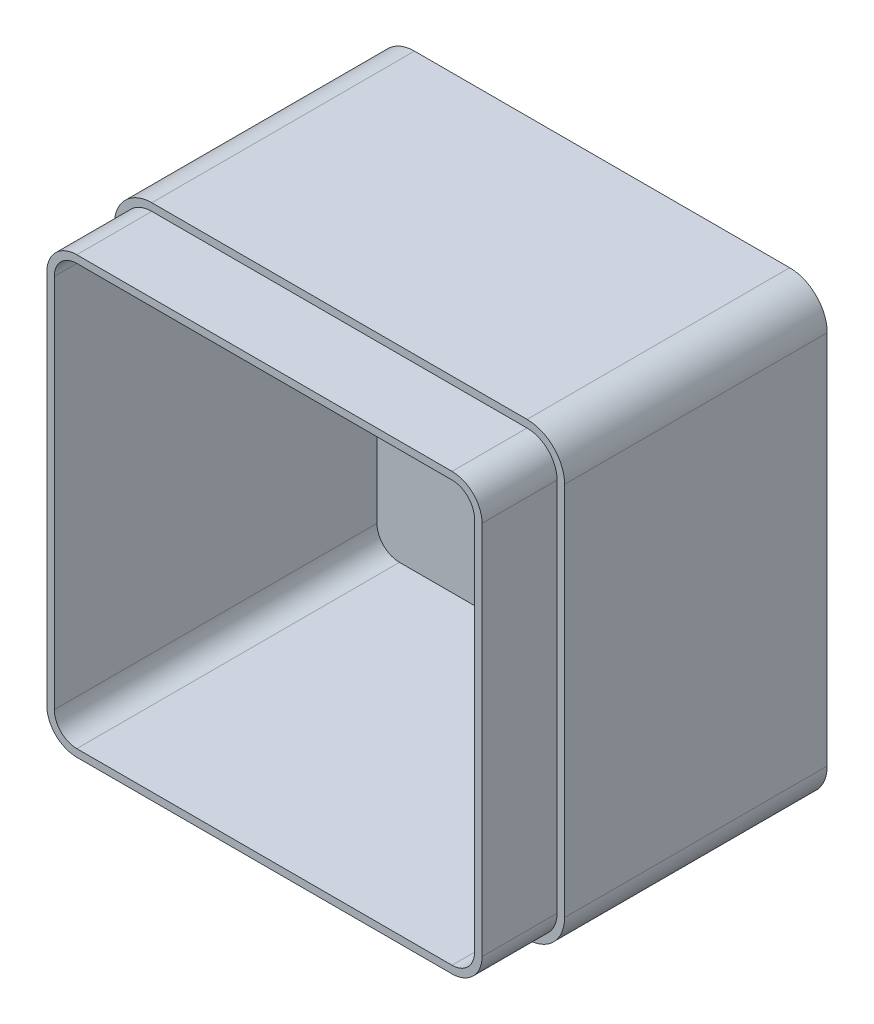
SolidWorks part; units mm, degrees
ref_plane "Спереди" through (0, 0, 0) normal (0, 0, 1) x (1, 0, 0)
ref_plane "Сверху" through (0, 0, 0) normal (0, 1, 0) x (1, 0, 0)
ref_plane "Справа" through (0, 0, 0) normal (1, 0, 0) x (0, 0, -1)
sketch "Эскиз1" plane through (0, 0, 0) normal (0, 0, 1) x (1, 0, 0)
  line L1 (0, 0) -> (120, 0)
  line L2 (0, 0) -> (0, 120)
  line L3 (0, 120) -> (120, 120)
  line L4 (120, 0) -> (120, 120)
  dimension "D1" = 120
  dimension "D2" = 120
extrude "Бобышка-Вытянуть1" add sketch "Эскиз1" along normal blind 90
fillet "Скругление1" radius 10 4 edges at (120, 120, 45) (0, 120, 45) (0, 0, 45) (120, 0, 45)
shell "Оболочка1" thickness 4
sketch "Эскиз2" plane through (0, 0, 90) normal (0, 0, 1) x (1, 0, 0)
  line L4 (120, 10) -> (120, 110)
  line L5 (110, 120) -> (10, 120)
  line L6 (0, 110) -> (0, 10)
  line L7 (10, 0) -> (110, 0)
  line L8 (120, 10) -> (120, 110)
  line L9 (110, 120) -> (10, 120)
  line L10 (0, 110) -> (0, 10)
  line L11 (10, 0) -> (110, 0)
  line L16 (118, 10) -> (118, 110)
  line L17 (110, 118) -> (10, 118)
  line L18 (2, 110) -> (2, 10)
  line L19 (10, 2) -> (110, 2)
  line L20 (118, 10) -> (118, 110)
  line L21 (110, 118) -> (10, 118)
  line L22 (2, 110) -> (2, 10)
  line L23 (10, 2) -> (110, 2)
  arc A4 (120, 110) -> (110, 120) centre (110, 110) ccw
  arc A5 (10, 120) -> (0, 110) centre (10, 110) ccw
  arc A6 (0, 10) -> (10, 0) centre (10, 10) ccw
  arc A7 (110, 0) -> (120, 10) centre (110, 10) ccw
  arc A8 (120, 110) -> (110, 120) centre (110, 110) ccw
  arc A9 (10, 120) -> (0, 110) centre (10, 110) ccw
  arc A10 (0, 10) -> (10, 0) centre (10, 10) ccw
  arc A11 (110, 0) -> (120, 10) centre (110, 10) ccw
  arc A16 (118, 110) -> (110, 118) centre (110, 110) ccw
  arc A17 (10, 118) -> (2, 110) centre (10, 110) ccw
  arc A18 (2, 10) -> (10, 2) centre (10, 10) ccw
  arc A19 (110, 2) -> (118, 10) centre (110, 10) ccw
  arc A20 (118, 110) -> (110, 118) centre (110, 110) ccw
  arc A21 (10, 118) -> (2, 110) centre (10, 110) ccw
  arc A22 (2, 10) -> (10, 2) centre (10, 10) ccw
  arc A23 (110, 2) -> (118, 10) centre (110, 10) ccw
  dimension "D1" = 0
  dimension "D2" = 2
extrude "Вырез-Вытянуть1" cut sketch "Эскиз2" against normal blind 20
